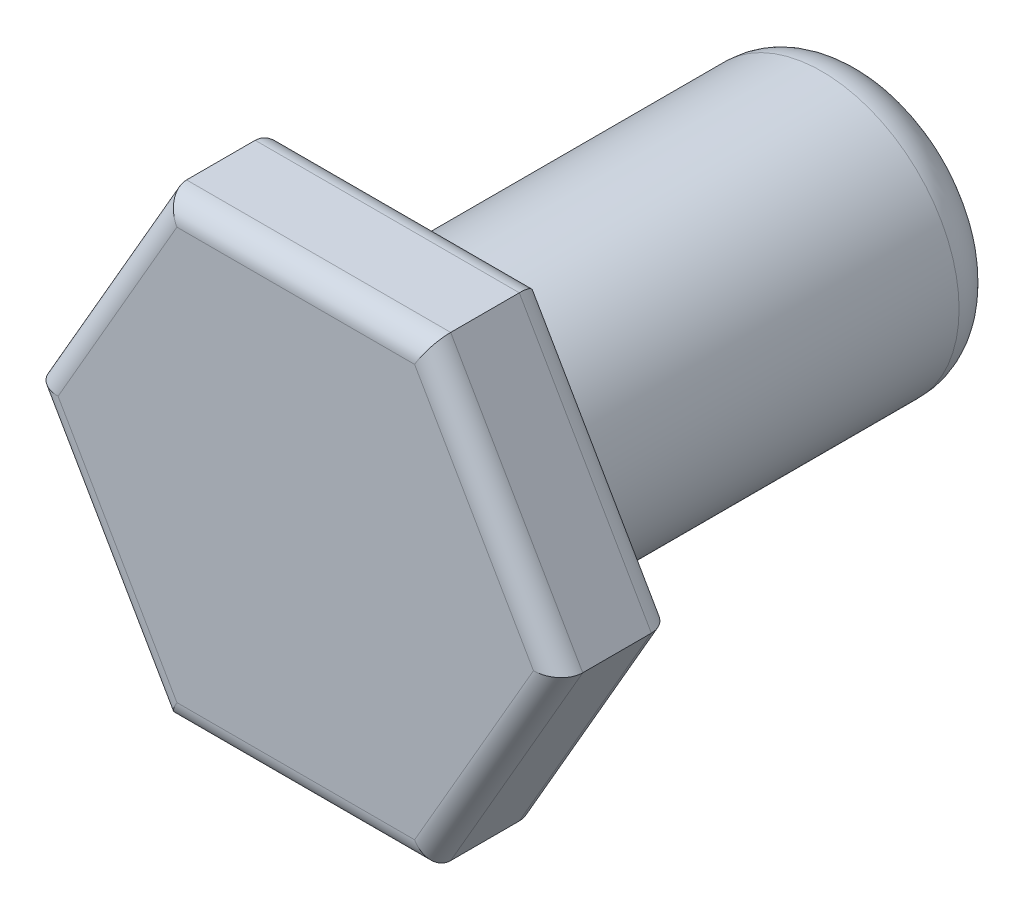
SolidWorks part; units mm, degrees
ref_plane "前视基准面" through (0, 0, 0) normal (0, 0, 1) x (1, 0, 0)
ref_plane "上视基准面" through (0, 0, 0) normal (0, 1, 0) x (1, 0, 0)
ref_plane "右视基准面" through (0, 0, 0) normal (1, 0, 0) x (0, 0, -1)
sketch "草图1" plane through (0, 0, 0) normal (0, 0, 1) x (1, 0, 0)
  circle A0 centre (0, 0) radius 6
  dimension "D1" = 12
extrude "凸台-拉伸1" add sketch "草图1" along normal blind 20
sketch "草图2" plane through (0, 0, 20) normal (0, 0, 1) x (1, 0, 0)
  line L1 (5.7735, -10) -> (11.547, 0)
  line L2 (11.547, 0) -> (5.7735, 10)
  line L3 (5.7735, 10) -> (-5.7735, 10)
  line L4 (-5.7735, 10) -> (-11.547, 0)
  line L5 (-11.547, 0) -> (-5.7735, -10)
  line L6 (-5.7735, -10) -> (5.7735, -10)
  circle A0 centre (0, 0) radius 10 construction
  dimension "D1" = 20
extrude "凸台-拉伸2" add sketch "草图2" along normal blind 5
fillet "圆角1" radius 2 1 edges at (6, 0, 0)
fillet "圆角2" radius 1 12 edges at (8.6603, 5, 20) (8.6603, -5, 20) (0, -10, 25) (0, -10, 20) (0, 10, 20) (-8.6603, 5, 20) (-8.6603, 5, 25) (-8.6603, -5, 25) (-8.6603, -5, 20) (8.6603, -5, 25) (8.6603, 5, 25) (0, 10, 25)
